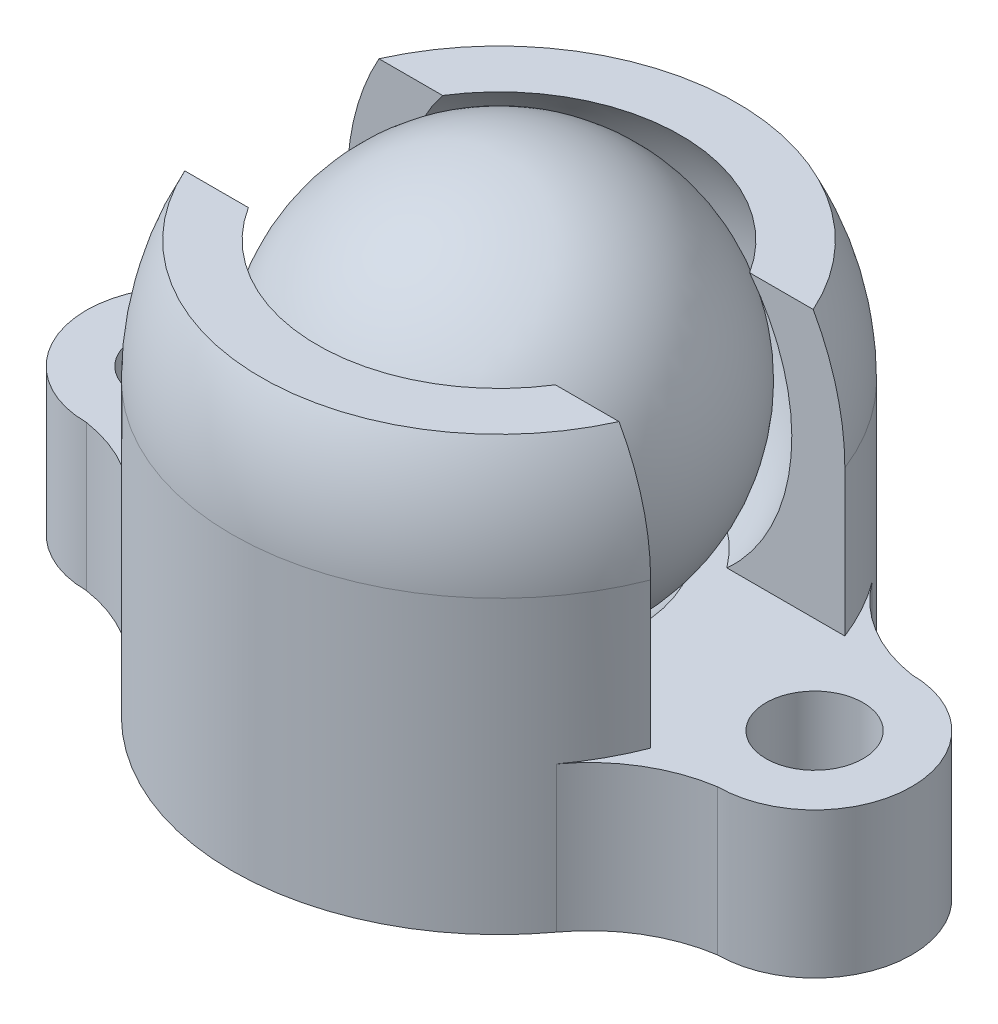
SolidWorks part; units mm, degrees
ref_plane "Front Plane" through (0, 0, 0) normal (0, 0, 1) x (1, 0, 0)
ref_plane "Top Plane" through (0, 0, 0) normal (0, 1, 0) x (1, 0, 0)
ref_plane "Right Plane" through (0, 0, 0) normal (1, 0, 0) x (0, 0, -1)
sketch "Sketch1" plane through (0, 0, 0) normal (0, 1, 0) x (1, 0, 0)
  line L0 (0, 5.5) -> (0, -5.5) construction
  line L2 (-6.5, 0) -> (7.0815, 0) construction
  circle A1 centre (-6.5, 0) radius 1
  arc A3 (-4.4371, -3.25) -> (4.4371, -3.25) centre (0, 0) ccw
  arc A4 (-6.5, 2) -> (-6.5, -2) centre (-6.5, 0) ccw
  arc A5 (-6.5, 2) -> (-4.4371, 3.25) centre (-6.9726, 5.1072) ccw
  arc A6 (-6.5, -2) -> (-4.4371, -3.25) centre (-6.9726, -5.1072) cw
  arc A7 (6.5, -2) -> (4.4371, -3.25) centre (6.9726, -5.1072) ccw
  arc A8 (6.5, 2) -> (4.4371, 3.25) centre (6.9726, 5.1072) cw
  arc A9 (6.5, 2) -> (6.5, -2) centre (6.5, 0) cw
  circle A10 centre (6.5, 0) radius 1
  arc A11 (4.4371, 3.25) -> (-4.4371, 3.25) centre (0, 0) ccw
  dimension "D1" = 11
  dimension "D2" = 2
  dimension "D4" = 6.5
  dimension "D3" = 2
extrude "Boss-Extrude1" add sketch "Sketch1" along normal blind 3
sketch "Sketch10" plane through (0, 0, 0) normal (0, 0, 1) x (1, 0, 0)
  line L0 (0, 2) -> (0, 11)
  line L1 (4.4371, 3) -> (-4.4371, 3) construction
  arc A0 (0, 11) -> (0, 2) centre (0, 6.5) cw
  dimension "D1" = 9
  dimension "D2" = 1
revolve "Cut-Revolve2" cut sketch "Sketch10" angle 360 about L0
sketch "Sketch13" plane through (0, 3, 0) normal (0, 1, 0) x (1, 0, 0)
  circle A0 centre (0, 0) radius 5.5
  arc A1 (4.4371, 3.25) -> (-4.4371, 3.25) centre (0, 0) ccw construction
sketch "Sketch16" plane through (0, 3, 0) normal (0, 1, 0) x (1, 0, 0)
  circle A0 centre (0, 0) radius 3.5
  dimension "D1" = 7
sketch "Sketch18" plane through (0, 0, 0) normal (1, 0, 0) x (0, 0, -1)
  line L0 (0, 10) -> (0, 2)
  line L2 (3.5, 3) -> (-3.5, 3) construction
  arc A0 (0, 2) -> (0, 10) centre (0, 6) ccw
  dimension "D1" = 8
  dimension "D2" = 1
sketch "Sketch19" plane through (0, 0, 0) normal (1, 0, 0) x (0, 0, -1)
  line L1 (5.5, 3) -> (-5.5, 3) construction
  line L2 (5.5, 6) -> (5.5, 3)
  line L4 (5.5, 3) -> (3.3541, 3)
  line L5 (3.7417, 8.5) -> (4.899, 8.5)
  arc A0 (0, 2) -> (0, 10) centre (0, 6) ccw construction
  arc A1 (5.5, 6) -> (4.899, 8.5) centre (0, 6) ccw
  arc A3 (3.3541, 3) -> (3.7417, 8.5) centre (0, 6) ccw
  point P23 (0, 6)
  dimension "D2" = 3
  dimension "D3" = 5.5
  dimension "D4" = 2.1459
revolve "Revolve6" add sketch "Sketch19" angle 360 about L0
sketch "Sketch20" plane through (0, 0, 0) normal (1, 0, 0) x (0, 0, -1)
  line L0 (-2, 3) -> (-2, 0) construction
  line L1 (-2, 3) -> (2, 3)
  line L2 (-2, 3) -> (-2, 8.5)
  line L3 (-2, 8.5) -> (2, 8.5)
  line L4 (2, 3) -> (2, 8.5)
  line L5 (0, 3) -> (-3.25, 3) construction
  line L6 (4.899, 8.5) -> (-4.899, 8.5) construction
extrude "Cut-Extrude2" cut sketch "Sketch20" against normal through all both and the other way through all
revolve "Revolve7" add sketch "Sketch18" angle 360 about L0
